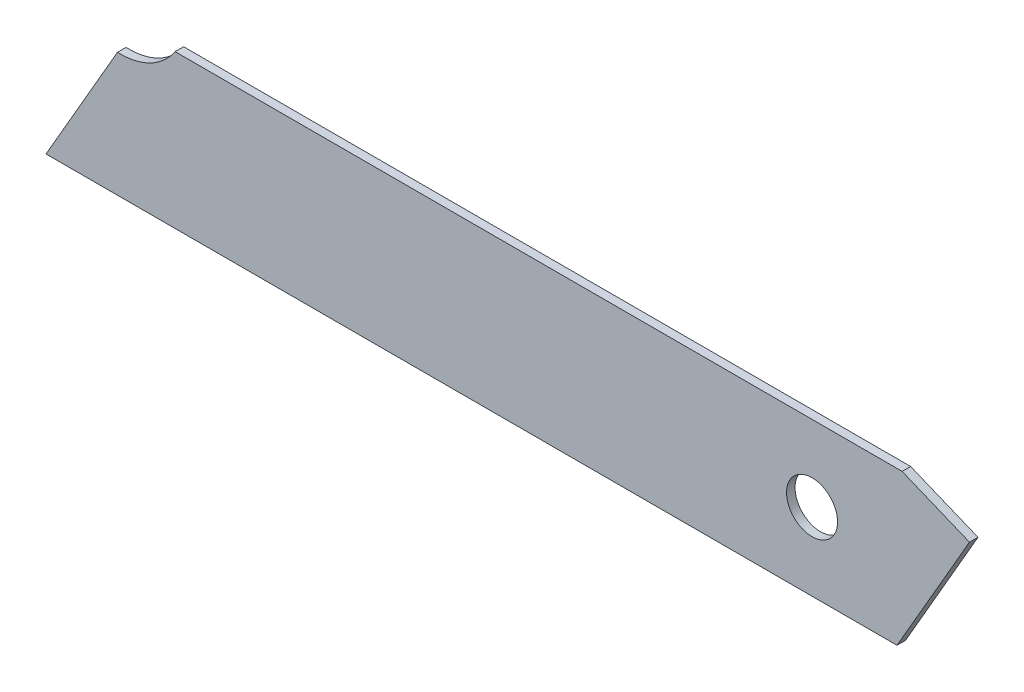
SolidWorks part; units mm, degrees
ref_plane "Płaszczyzna przednia" through (0, 0, 0) normal (0, 0, 1) x (1, 0, 0)
ref_plane "Płaszczyzna górna" through (0, 0, 0) normal (0, 1, 0) x (1, 0, 0)
ref_plane "Płaszczyzna prawa" through (0, 0, 0) normal (1, 0, 0) x (0, 0, -1)
sketch "Sketch1" plane through (0, 0, 0) normal (0, 0, 1) x (1, 0, 0)
  line L0 (0, 0) -> (100, 0)
  line L1 (10.3923, 18) -> (110.3923, 18)
  line L2 (10.3923, 18) -> (0, 0)
  line L3 (110.3923, 18) -> (100, 0)
  line L4 (100.6014, 18) -> (108.5163, 14.7507)
  arc A0 (8.3995, 14.5484) -> (15.167, 18) centre (8.7591, 22.2037) ccw
  circle A1 centre (90.0158, 9.062) radius 3
  point P8 (108.5163, 14.7507)
  dimension "D1" = 100
  dimension "D2" = 18
  dimension "D4" = 60
extrude "Boss-Extrude1" add sketch "Sketch1" along normal blind 1 contours A0 L2 L0 L3 L4 L1 A1
